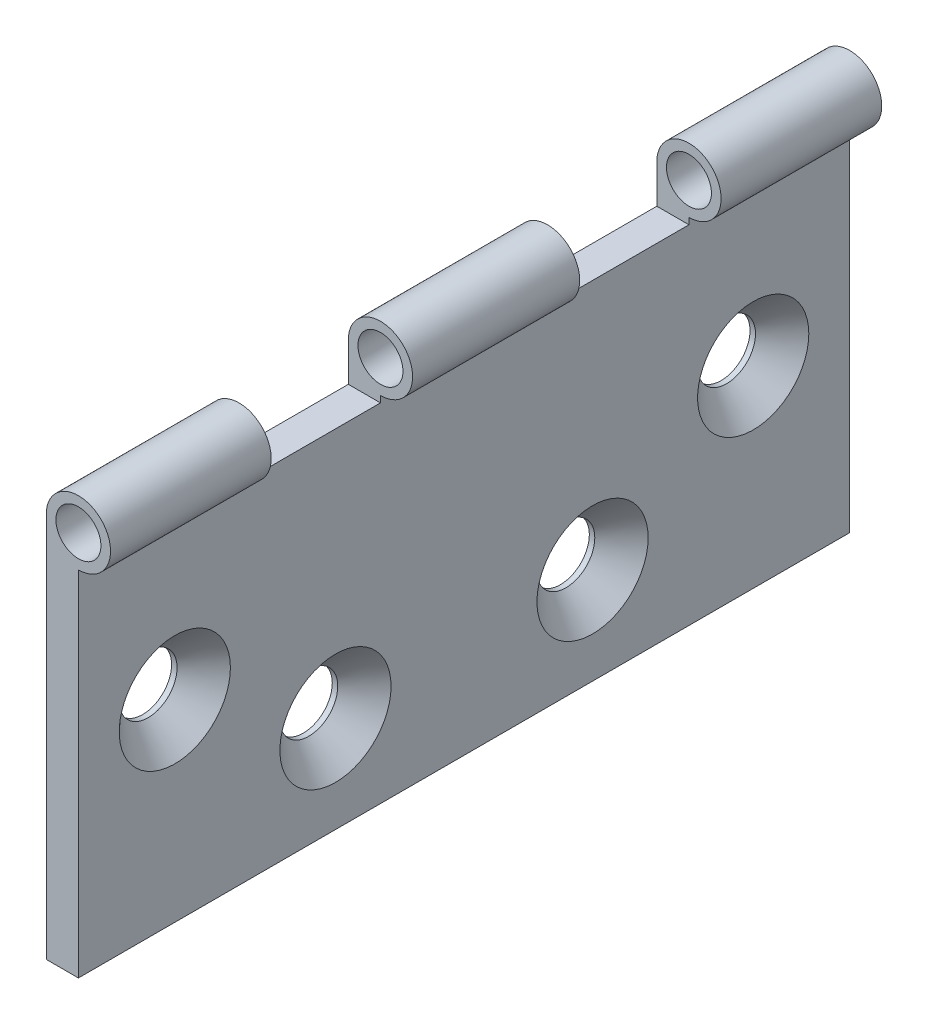
SolidWorks part; units mm, degrees
ref_plane "Front Plane" through (0, 0, 0) normal (0, 0, 1) x (1, 0, 0)
ref_plane "Top Plane" through (0, 0, 0) normal (0, 1, 0) x (1, 0, 0)
ref_plane "Right Plane" through (0, 0, 0) normal (1, 0, 0) x (0, 0, -1)
sketch "Эскиз1" plane through (0, 0, 0) normal (0, 0, 1) x (1, 0, 0)
  line L0 (0, 0) -> (0, 60)
  dimension "D1" = 60
extrude "Вытянуть-Тонкостенный1" add sketch "Эскиз1" along normal mid plane 120 thin
sketch "Эскиз2" plane through (0, 0, 60) normal (0, 0, 1) x (1, 0, 0)
  circle A0 centre (5, 60) radius 5
sweep "По траектории1" add profiles "Эскиз2" path edge at (5, 60, 0)
sketch "Эскиз4" plane through (0, 0, 60) normal (0, 0, 1) x (1, 0, 0)
  circle A0 centre (5, 60) radius 3.5
  arc A1 (5, 55) -> (0, 60) centre (5, 60) ccw construction
extrude "Вырез-Вытянуть1" cut sketch "Эскиз4" against normal through all
hole_wizard "Зенковка для  винта с плоской головкой M81" positions "Эскиз6" profile "Эскиз5" countersink size "M8" standard "Ansi Metric" end condition through all
sketch "Эскиз6" plane through (5, 0, 0) normal (1, 0, 0) x (0, 0, -1)
  point P0 (-45, 30)
  point P2 (-20, 15)
  dimension "D1" = 30
  dimension "D2" = 15
  dimension "D3" = 15
  dimension "D4" = 40
sketch "Эскиз5" plane through (5, 30, 45) normal (0, 1, 0) x (0, 0, -1)
  line L0 (0, 0) -> (0, 5)
  line L1 (0, 5) -> (4.5, 5)
  line L2 (4.5, 5) -> (4.5, 4.15)
  line L3 (4.5, 4.15) -> (8.65, 0)
  line L5 (8.65, 0) -> (0, 0)
  line L6 (-4.5, 4.15) -> (-8.65, 0) construction
  line L11 (0, -6.35) -> (0, 107.95) construction
  dimension "Диаметр сквозного отверстия" = 9
  dimension "Глубина сквозного отверстия" = 5
  dimension "Диаметр передней зенковки" = 17.3
  dimension "Угол передней зенковки" = 90
mirror "Зеркальное отражение1" about plane through (0, 0, 0) normal (0, 0, 1) of "Зенковка для  винта с плоской головкой M81"
sketch "компоновка для вырезов" plane through (5, 0, 0) normal (1, 0, 0) x (0, 0, -1)
  line L0 (-60, 65) -> (-60, 55) construction
  line L1 (60, 55) -> (60, 65) construction
  line L2 (-60, 65) -> (-60, 54)
  line L3 (60, 54) -> (-60, 54)
  line L4 (60, 54) -> (-60, 54)
  line L5 (60, 54) -> (60, 65)
  line L6 (-36, 65) -> (-36, 54)
  line L7 (60, 65) -> (-60, 65) construction
  line L8 (-12, 65) -> (-12, 54)
  line L9 (0, 81.1737) -> (0, 0) construction
  line L10 (12, 65) -> (12, 54)
  line L11 (36, 65) -> (36, 54)
  dimension "D2" = 24
  dimension "D3" = 24
  dimension "D1" = 1
sketch "Эскиз8" plane through (5, 0, 0) normal (1, 0, 0) x (0, 0, -1)
  line L1 (60, 54) -> (-60, 54) construction
  line L3 (-13, 54) -> (-35, 54)
  line L4 (35, 54) -> (13, 54)
  line L6 (35, 65) -> (13, 65)
  line L7 (-13, 65) -> (-35, 65)
  line L9 (-35, 65) -> (-35, 54)
  line L10 (-35, 65) -> (-35, 54)
  line L12 (35, 65) -> (35, 54)
  line L13 (35, 65) -> (35, 54)
  line L15 (13, 65) -> (13, 54)
  line L16 (13, 65) -> (13, 54)
  line L18 (-13, 65) -> (-13, 54)
  line L19 (-13, 65) -> (-13, 54)
  point P4 (-33.044, 41.9765)
  dimension "D2" = 1
  dimension "D3" = 1
  dimension "D4" = 1
  dimension "D5" = 1
extrude "Вырез-Вытянуть3" cut sketch "Эскиз8" against normal through all both and the other way through all
equation "\"D1@Эскиз6\"= \"D1@Эскиз1\" / 2"
equation "\"D4@Эскиз6\"= \"D1@Вытянуть-Тонкостенный1\" / 3"
equation "\"D2@компоновка для вырезов\"= \"D1@Вытянуть-Тонкостенный1\"/5"
equation "\"D3@компоновка для вырезов\"= \"D1@Вытянуть-Тонкостенный1\" / 5"
